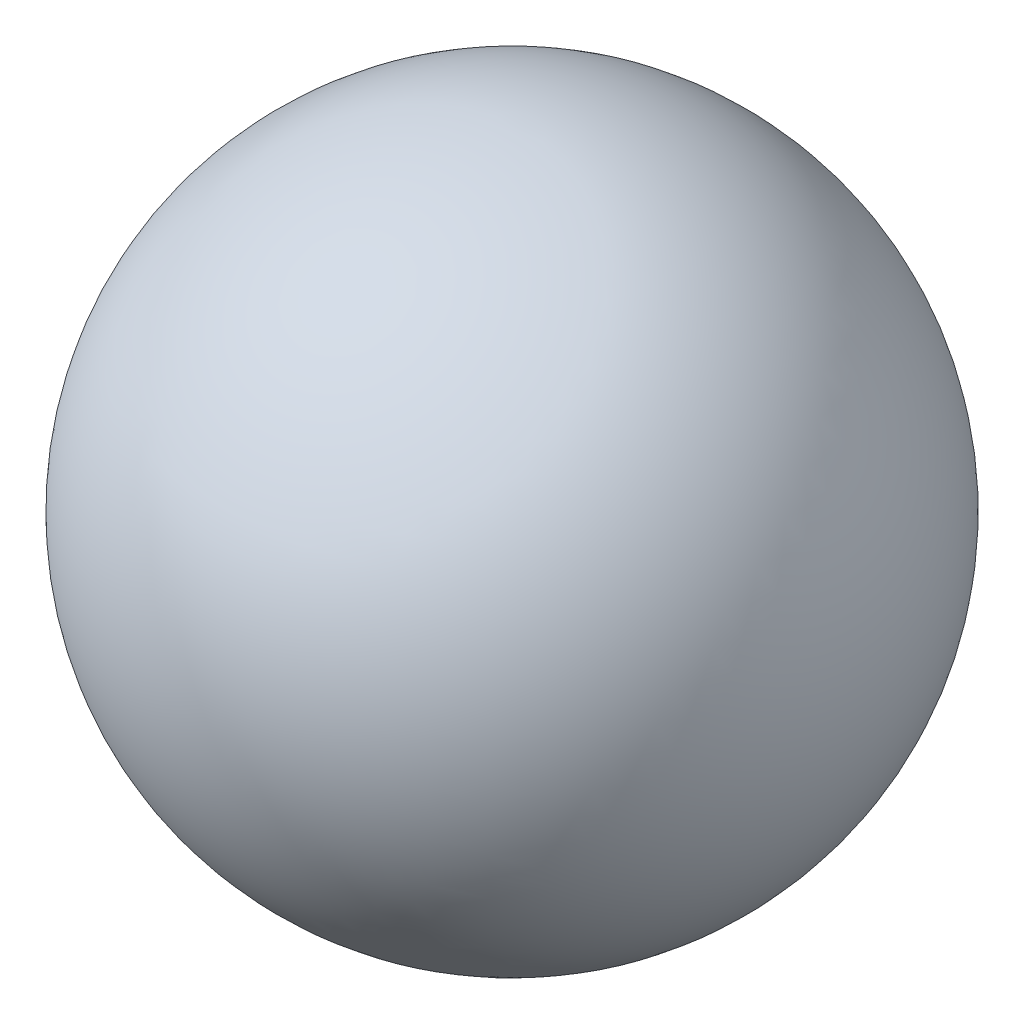
SolidWorks part; units mm, degrees
ref_plane "Front Plane" through (0, 0, 0) normal (0, 0, 1) x (1, 0, 0)
ref_plane "Top Plane" through (0, 0, 0) normal (0, 1, 0) x (1, 0, 0)
ref_plane "Right Plane" through (0, 0, 0) normal (1, 0, 0) x (0, 0, -1)
sketch "Sketch1" plane through (0, 0, 0) normal (0, 0, 1) x (1, 0, 0)
  line L0 (0, 0) -> (0, 62.7451) construction
  line L1 (0, 60) -> (0, 58)
  line L2 (0, 2) -> (0, 0)
  arc A0 (0, 0) -> (0, 60) centre (0, 30) ccw
  arc A1 (0, 2) -> (0, 58) centre (0, 30) ccw
  dimension "D1" = 30
  dimension "D2" = 2
revolve "Revolve1" add sketch "Sketch1" angle 360 about L0
sketch "Sketch2" plane through (0, 0, 0) normal (0, 0, 1) x (1, 0, 0)
  circle A0 centre (0, 15) radius 2.5
  dimension "D1" = 5
  dimension "D2" = 15
extrude "Cut-Extrude1" cut sketch "Sketch2" against normal up to surface (25.8602 mm away)
